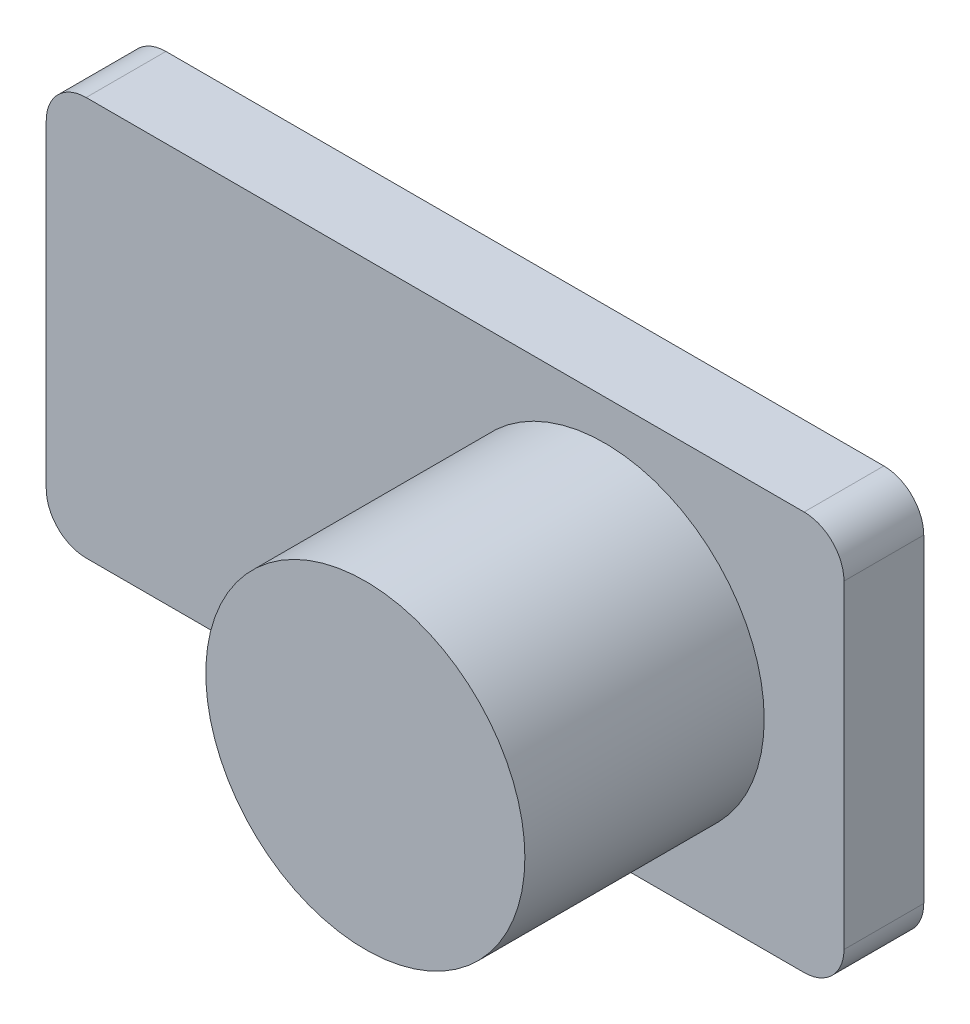
SolidWorks part; units mm, degrees
ref_plane "Front Plane" through (0, 0, 0) normal (0, 0, 1) x (1, 0, 0)
ref_plane "Top Plane" through (0, 0, 0) normal (0, 1, 0) x (1, 0, 0)
ref_plane "Right Plane" through (0, 0, 0) normal (1, 0, 0) x (0, 0, -1)
sketch "Sketch1" plane through (0, 0, 0) normal (0, 0, 1) x (1, 0, 0)
  line L0 (0, -58.0169) -> (0, 0) construction
  line L1 (-10, -22.0965) -> (10, -22.0965)
  line L2 (-10, -22.0965) -> (-10, -32.0965)
  line L3 (-10, -32.0965) -> (10, -32.0965)
  line L4 (10, -22.0965) -> (10, -32.0965)
  line L5 (-10, -27.0965) -> (10, -27.0965) construction
  dimension "D1" = 10
  dimension "D2" = 20
  dimension "D3" = 10
extrude "Boss-Extrude1" add sketch "Sketch1" along normal blind 2
sketch "Sketch2" plane through (0, 0, 2) normal (0, 0, 1) x (1, 0, 0)
  line L0 (0, -22.0965) -> (0, -32.0965) construction
  line L1 (10, -22.0965) -> (-10, -22.0965) construction
  line L2 (-10, -32.0965) -> (10, -32.0965) construction
  line L3 (0, -27.0965) -> (9.9536, -27.0965) construction
  circle A0 centre (4, -27.0965) radius 4
extrude "Boss-Extrude2" add sketch "Sketch2" along normal blind 6
fillet "Fillet1" radius 1 4 edges at (-10, -32.0965, 1) (-10, -22.0965, 1) (10, -32.0965, 1) (10, -22.0965, 1)
